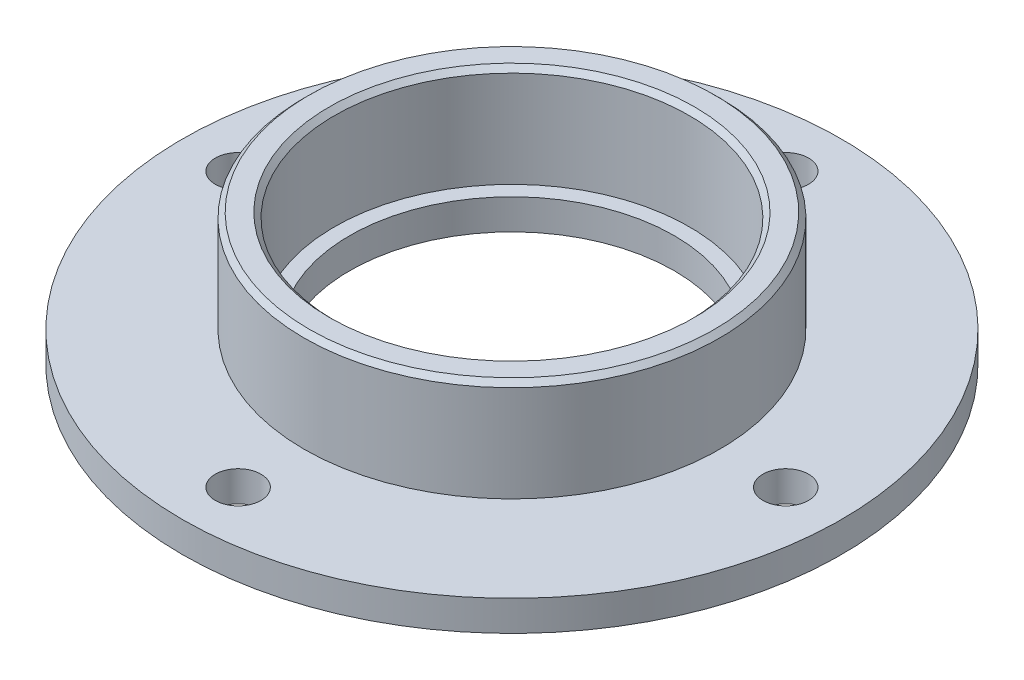
SolidWorks part; units mm, degrees
material "AISI 316 Stainless Steel Sheet (SS)"
ref_plane "Front Plane" through (0, 0, 0) normal (0, 0, 1) x (1, 0, 0)
ref_plane "Top Plane" through (0, 0, 0) normal (0, 1, 0) x (1, 0, 0)
ref_plane "Right Plane" through (0, 0, 0) normal (1, 0, 0) x (0, 0, -1)
sketch "Sketch1" plane through (0, 0, 0) normal (0, 1, 0) x (1, 0, 0)
  line L0 (0, -44.7868) -> (0, 44.7868) construction
  circle A0 centre (0, 0) radius 32.5
  circle A2 centre (0, 0) radius 16
  circle A3 centre (0, 27) radius 1
  circle A9 centre (27, 0) radius 1
  circle A10 centre (0, -27) radius 1
  circle A11 centre (-27, 0) radius 1
  point P17 (0, 0)
  point P21 (0, 0)
  dimension "D1" = 65
  dimension "D2" = 32
  dimension "D3" = 2
  dimension "D4" = 27
  dimension "D5" = 4
extrude "Boss-Extrude1" add sketch "Sketch1" along normal blind 3
sketch "Sketch2" plane through (0, 3, 0) normal (0, 1, 0) x (1, 0, 0)
  circle A0 centre (0, 0) radius 17.5
  circle A1 centre (0, 0) radius 20.5
  dimension "D1" = 35
  dimension "D2" = 41
extrude "Boss-Extrude2" add sketch "Sketch2" along normal blind 10
sketch "Sketch7" plane through (0, 3, 0) normal (0, 1, 0) x (1, 0, 0)
  point P0 (0, 27)
  point P3 (27, 0)
  point P6 (0, -27)
  point P9 (-27, 0)
hole_wizard "M4 Clearance Hole2" positions "Sketch7" profile "Sketch6" hole size "M4" standard "ANSI Metric"
sketch "Sketch6" plane through (0, 3, -27) normal (1, 0, 0) x (0, 0, 1)
  line L0 (0, 0) -> (0, 12.8519)
  line L1 (0, 12.8519) -> (2.25, 11.5)
  line L2 (2.25, 11.5) -> (2.25, 0)
  line L5 (2.25, 0) -> (0, 0)
  line L10 (0, 12.8519) -> (-2.25, 11.5) construction
  line L11 (0, -6.35) -> (0, 107.95) construction
  dimension "Hole Dia." = 4.5
  dimension "Hole Depth" = 11.5
  dimension "Drill Angle" = 118
chamfer "Chamfer1" distance 0.5 angle 45 2 edges at (0, 13, 20.5) (0, 13, 17.5)
